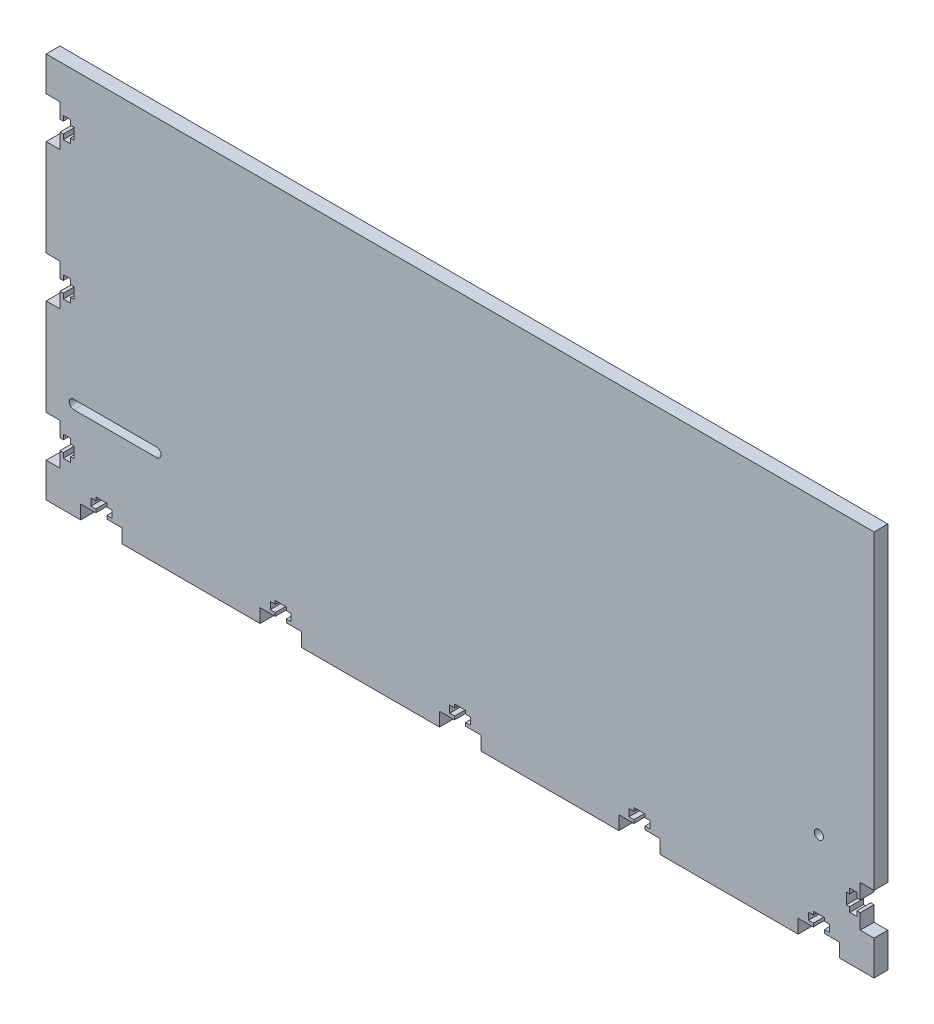
SolidWorks part; units mm, degrees
ref_plane "Front Plane" through (0, 0, 0) normal (0, 0, 1) x (1, 0, 0)
ref_plane "Top Plane" through (0, 0, 0) normal (0, 1, 0) x (1, 0, 0)
ref_plane "Right Plane" through (0, 0, 0) normal (1, 0, 0) x (0, 0, -1)
sketch "Sketch1" plane through (0, 0, 0) normal (0, 0, 1) x (1, 0, 0)
  line L1 (0, 0) -> (381, 0)
  line L2 (0, 0) -> (0, 177.8)
  line L3 (0, 177.8) -> (381, 177.8)
  line L4 (381, 0) -> (381, 177.8)
  dimension "D1" = 381
  dimension "D2" = 177.8
extrude "Boss-Extrude1" add sketch "Sketch1" along normal blind 6.35
sketch "Sketch2" plane through (0, 0, 6.35) normal (0, 0, 1) x (1, 0, 0)
  line L0 (12.7, 44.45) -> (50.8, 44.45) construction
  line L1 (12.7, 46.55) -> (50.8, 46.55)
  line L2 (12.7, 42.35) -> (50.8, 42.35)
  line L3 (0, 0) -> (381, 0) construction
  line L5 (0, 177.8) -> (0, 0) construction
  arc A0 (12.7, 46.55) -> (12.7, 42.35) centre (12.7, 44.45) ccw
  arc A1 (50.8, 42.35) -> (50.8, 46.55) centre (50.8, 44.45) ccw
  point P2 (31.75, 44.45)
  dimension "D2" = 38.1
  dimension "D1" = 4.2
  dimension "D3" = 44.45
  dimension "D4" = 31.75
extrude "Cut-Extrude1" cut sketch "Sketch2" against normal through all
ref_plane "Plane1" through (190.5, 0, 0) normal (-1, 0, 0) x (0, 0, 1)
sketch "Sketch6" plane through (0, 0, 6.35) normal (0, 0, 1) x (1, 0, 0)
  line L2 (15.875, 0) -> (34.925, 0)
  line L3 (15.875, 0) -> (15.875, 6.35)
  line L4 (15.875, 6.35) -> (22.86, 6.35)
  line L5 (34.925, 0) -> (34.925, 6.35)
  line L6 (0, 177.8) -> (0, 0) construction
  line L7 (22.86, 6.35) -> (22.86, 7.874)
  line L8 (22.86, 12.7) -> (27.94, 12.7)
  line L9 (27.94, 6.35) -> (27.94, 7.874)
  line L10 (22.86, 11.176) -> (22.86, 12.7)
  line L11 (20.574, 11.176) -> (22.86, 11.176)
  line L12 (20.574, 11.176) -> (20.574, 7.874)
  line L13 (20.574, 7.874) -> (22.86, 7.874)
  line L14 (30.226, 11.176) -> (30.226, 7.874)
  line L15 (27.94, 11.176) -> (30.226, 11.176)
  line L16 (27.94, 11.176) -> (27.94, 12.7)
  line L17 (27.94, 7.874) -> (30.226, 7.874)
  line L18 (27.94, 6.35) -> (34.925, 6.35)
  line L19 (0, 0) -> (381, 0) construction
  point P8 (25.4, 12.7)
  dimension "D1" = 6.35
  dimension "D2" = 19.05
  dimension "D3" = 6.35
  dimension "D4" = 5.08
  dimension "D5" = 25.4
  dimension "D6" = 9.652
  dimension "D7" = 3.302
  dimension "D10" = 15.875
extrude "Cut-Extrude2" cut sketch "Sketch6" against normal through all
pattern_linear "LPattern1" count 5 spacing 82.55 along (1, 0, 0) of "Cut-Extrude2"
sketch "Sketch7" plane through (0, 0, 6.35) normal (0, 0, 1) x (1, 0, 0)
  line L0 (381, 0) -> (381, 177.8) construction
  line L2 (355.6, 44.45) -> (381, 44.45) construction
  circle A0 centre (355.6, 44.45) radius 2.1
  dimension "D1" = 4.2
  dimension "D2" = 25.4
  dimension "D3" = 44.45
extrude "Cut-Extrude3" cut sketch "Sketch7" against normal through all
sketch "Sketch8" plane through (0, 0, 6.35) normal (0, 0, 1) x (1, 0, 0)
  line L0 (0, 161.925) -> (0, 142.875)
  line L1 (0, 161.925) -> (6.35, 161.925)
  line L2 (6.35, 161.925) -> (6.35, 154.94)
  line L3 (0, 142.875) -> (6.35, 142.875)
  line L4 (6.35, 154.94) -> (7.874, 154.94)
  line L5 (12.7, 154.94) -> (12.7, 149.86)
  line L6 (6.35, 149.86) -> (7.874, 149.86)
  line L7 (11.176, 154.94) -> (12.7, 154.94)
  line L8 (11.176, 157.226) -> (11.176, 154.94)
  line L9 (11.176, 157.226) -> (7.874, 157.226)
  line L10 (7.874, 157.226) -> (7.874, 154.94)
  line L11 (11.176, 147.574) -> (7.874, 147.574)
  line L12 (11.176, 149.86) -> (11.176, 147.574)
  line L13 (11.176, 149.86) -> (12.7, 149.86)
  line L14 (7.874, 149.86) -> (7.874, 147.574)
  line L15 (6.35, 149.86) -> (6.35, 142.875)
  line L16 (0, 177.8) -> (0, 0) construction
  line L17 (381, 177.8) -> (0, 177.8) construction
  point P8 (12.7, 152.4)
  point P21 (0, 0)
  dimension "D1" = 6.35
  dimension "D2" = 5.08
  dimension "D3" = 6.35
  dimension "D4" = 9.652
  dimension "D5" = 3.302
  dimension "D6" = 15.875
  dimension "D7" = 19.05
extrude "Cut-Extrude4" cut sketch "Sketch8" against normal through all
pattern_linear "LPattern3" count 2 spacing 63.5 along (0, -1, 0) of "Cut-Extrude4"
sketch "Sketch9" plane through (0, 0, 6.35) normal (0, 0, 1) x (1, 0, 0)
  line L0 (0, 34.925) -> (0, 15.875)
  line L1 (0, 34.925) -> (6.35, 34.925)
  line L2 (6.35, 34.925) -> (6.35, 27.94)
  line L3 (0, 15.875) -> (6.35, 15.875)
  line L4 (6.35, 27.94) -> (7.874, 27.94)
  line L5 (12.7, 27.94) -> (12.7, 22.86)
  line L6 (6.35, 22.86) -> (7.874, 22.86)
  line L7 (11.176, 27.94) -> (12.7, 27.94)
  line L8 (11.176, 30.226) -> (11.176, 27.94)
  line L9 (11.176, 30.226) -> (7.874, 30.226)
  line L10 (7.874, 30.226) -> (7.874, 27.94)
  line L11 (11.176, 20.574) -> (7.874, 20.574)
  line L12 (11.176, 22.86) -> (11.176, 20.574)
  line L13 (11.176, 22.86) -> (12.7, 22.86)
  line L14 (7.874, 22.86) -> (7.874, 20.574)
  line L15 (6.35, 22.86) -> (6.35, 15.875)
  line L16 (0, 79.375) -> (0, 0) construction
  line L17 (0, 79.375) -> (6.35, 79.375) construction
  point P8 (12.7, 25.4)
  dimension "D1" = 6.35
  dimension "D2" = 5.08
  dimension "D3" = 6.35
  dimension "D4" = 9.652
  dimension "D5" = 3.302
  dimension "D6" = 19.05
  dimension "D7" = 63.5
  dimension "D8" = 12.7
extrude "Cut-Extrude5" cut sketch "Sketch9" against normal through all
mirror "Mirror2" about plane through (190.5, 0, 0) normal (-1, 0, 0) of "Cut-Extrude5"
